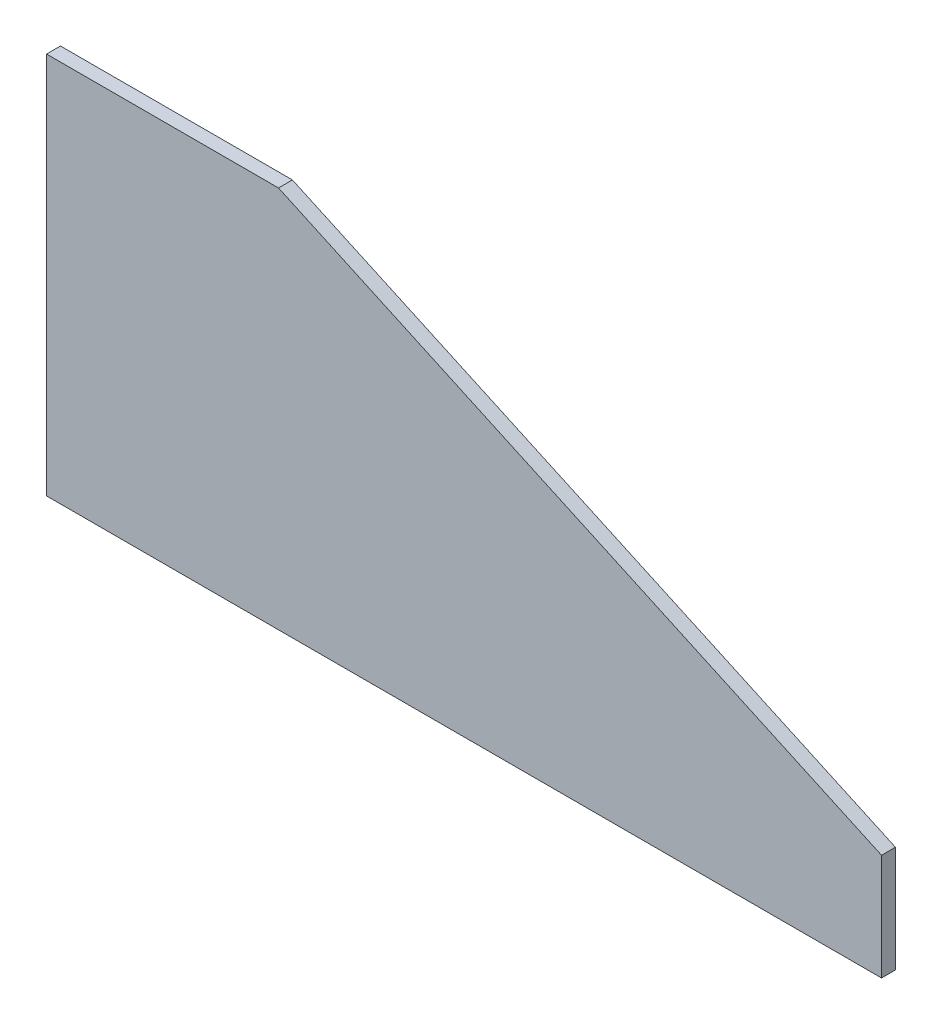
SolidWorks part; units mm, degrees
material "Hexcel AS4C (3000 Filaments)"
ref_plane "Front Plane" through (0, 0, 0) normal (0, 0, 1) x (1, 0, 0)
ref_plane "Top Plane" through (0, 0, 0) normal (0, 1, 0) x (1, 0, 0)
ref_plane "Right Plane" through (0, 0, 0) normal (1, 0, 0) x (0, 0, -1)
sketch "Sketch1" plane through (0, 0, 0) normal (0, 0, 1) x (1, 0, 0)
  line L0 (-13.3329, 13.75) -> (30, -6.1109)
  line L1 (-30, -13.75) -> (30, -13.75)
  line L2 (-30, -13.75) -> (-30, 13.75)
  line L3 (-30, 13.75) -> (-13.3329, 13.75)
  line L4 (30, -13.75) -> (30, -6.1109)
  line L5 (-30, -13.75) -> (30, 13.75) construction
  line L6 (-30, 13.75) -> (30, -13.75) construction
  point P0 (0, 0)
  point P8 (0, 0)
  point P9 (0, 0)
  dimension "D1" = 60
  dimension "D2" = 27.5
  dimension "D3" = 43.3329
extrude "Boss-Extrude1" add sketch "Sketch1" along normal blind 1
